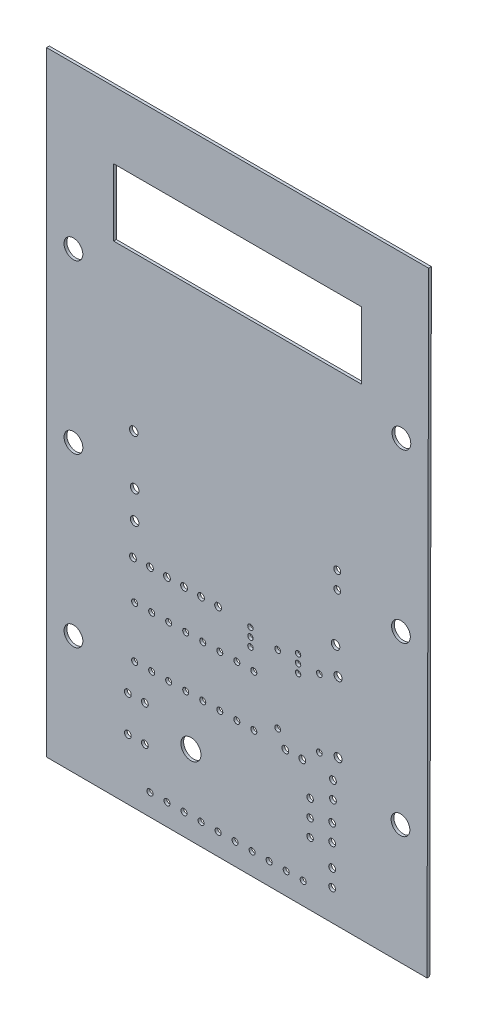
SolidWorks part; units mm, degrees
ref_plane "Front Plane" through (0, 0, 0) normal (0, 0, 1) x (1, 0, 0)
ref_plane "Top Plane" through (0, 0, 0) normal (0, 1, 0) x (1, 0, 0)
ref_plane "Right Plane" through (0, 0, 0) normal (1, 0, 0) x (0, 0, -1)
sketch "Sketch1" plane through (0, 0, 0) normal (0, 0, 1) x (1, 0, 0)
  line L0 (123.1803, 67.5548) -> (123.4282, 159.3916) construction
  line L1 (127.4282, 135.3808) -> (70.4281, 135.3808) construction
  line L2 (74.4281, 159.3813) -> (74.4384, 67.7095) construction
  line L3 (70.4384, 67.7091) -> (127.1803, 67.544)
  line L4 (70.4281, 159.3808) -> (70.4384, 67.7091)
  line L5 (127.1803, 67.544) -> (127.4282, 159.3808)
  line L6 (127.4282, 159.3808) -> (70.4281, 159.3808)
  line L7 (127.4282, 110.3808) -> (70.4281, 110.3808) construction
  line L8 (127.4282, 85.3808) -> (70.4281, 85.3808) construction
  line L9 (117.4309, 149.3808) -> (80.435, 149.3808)
  line L10 (117.4309, 149.3808) -> (117.4309, 139.3808)
  line L11 (117.4309, 139.3808) -> (80.435, 139.3808)
  line L12 (80.435, 149.3808) -> (80.435, 139.3808)
  circle A0 centre (113.792, 110.998) radius 0.508
  circle A1 centre (113.792, 113.538) radius 0.508
  circle A2 centre (113.919, 99.845) radius 0.6
  circle A3 centre (113.538, 103.759) radius 0.635
  circle A4 centre (107.95, 99.822) radius 0.4
  circle A5 centre (111.125, 98.806) radius 0.425
  circle A6 centre (113.919, 89.385) radius 0.6
  circle A7 centre (107.95, 98.552) radius 0.4
  circle A8 centre (111.125, 88.646) radius 0.425
  circle A9 centre (104.902, 98.806) radius 0.425
  circle A10 centre (107.95, 97.282) radius 0.4
  circle A11 centre (100.838, 99.695) radius 0.4
  circle A12 centre (100.838, 98.425) radius 0.4
  circle A13 centre (101.346, 94.234) radius 0.45
  circle A14 centre (104.902, 88.646) radius 0.425
  circle A15 centre (100.838, 97.155) radius 0.4
  circle A16 centre (101.346, 86.614) radius 0.45
  circle A17 centre (113.157, 86.106) radius 0.508
  circle A18 centre (113.157, 83.566) radius 0.508
  circle A19 centre (109.742, 82.0512) radius 0.4826
  circle A20 centre (113.03, 80.518) radius 0.508
  circle A21 centre (113.03, 74.676) radius 0.508
  circle A22 centre (113.03, 72.136) radius 0.508
  circle A23 centre (109.742, 79.5112) radius 0.4826
  circle A24 centre (113.03, 77.978) radius 0.508
  circle A25 centre (108.585, 86.487) radius 0.508
  circle A26 centre (109.742, 76.9712) radius 0.4826
  circle A27 centre (98.806, 86.614) radius 0.45
  circle A28 centre (106.045, 86.487) radius 0.508
  circle A29 centre (106.172, 70.866) radius 0.45
  circle A30 centre (108.712, 70.866) radius 0.45
  circle A31 centre (101.092, 70.866) radius 0.45
  circle A32 centre (103.632, 70.866) radius 0.45
  circle A33 centre (96.266, 94.234) radius 0.45
  circle A34 centre (96.012, 99.949) radius 0.508
  circle A35 centre (93.726, 94.234) radius 0.45
  circle A36 centre (90.932, 99.949) radius 0.508
  circle A37 centre (93.472, 99.949) radius 0.508
  circle A38 centre (98.806, 94.234) radius 0.45
  circle A39 centre (93.726, 86.614) radius 0.45
  circle A40 centre (88.646, 94.234) radius 0.45
  circle A41 centre (91.186, 94.234) radius 0.45
  circle A42 centre (83.566, 104.775) radius 0.635
  circle A43 centre (85.852, 99.949) radius 0.508
  circle A44 centre (83.439, 116.332) radius 0.635
  circle A45 centre (83.566, 108.966) radius 0.635
  circle A46 centre (88.392, 99.949) radius 0.508
  circle A47 centre (86.106, 94.234) radius 0.45
  circle A48 centre (83.312, 99.949) radius 0.508
  circle A49 centre (83.566, 94.234) radius 0.45
  circle A50 centre (91.186, 86.614) radius 0.45
  circle A51 centre (96.266, 86.614) radius 0.45
  circle A52 centre (88.646, 86.614) radius 0.45
  circle A53 centre (91.962, 79.5112) radius 1.5
  circle A54 centre (96.012, 70.866) radius 0.45
  circle A55 centre (98.552, 70.866) radius 0.45
  circle A56 centre (90.932, 70.866) radius 0.45
  circle A57 centre (93.472, 70.866) radius 0.45
  circle A58 centre (86.106, 86.614) radius 0.45
  circle A59 centre (85.09, 82.042) radius 0.508
  circle A60 centre (83.566, 86.614) radius 0.45
  circle A61 centre (82.55, 82.042) radius 0.508
  circle A62 centre (85.852, 70.866) radius 0.45
  circle A63 centre (88.392, 70.866) radius 0.45
  circle A64 centre (82.55, 76.708) radius 0.508
  circle A65 centre (85.09, 76.708) radius 0.508
  circle A66 centre (123.3634, 135.3808) radius 1.4
  circle A67 centre (74.4308, 135.3808) radius 1.4
  circle A68 centre (74.4336, 110.3808) radius 1.4
  circle A69 centre (123.2959, 110.3808) radius 1.4
  circle A70 centre (74.4364, 85.3808) radius 1.4
  circle A71 centre (123.2284, 85.3808) radius 1.4
  dimension "D3" = 2.8
  dimension "D5" = 2.8
  dimension "D1" = 4
  dimension "D4" = 4
  dimension "D2" = 24
  dimension "D6" = 25
  dimension "D7" = 25
extrude "Boss-Extrude1" add sketch "Sketch1" against normal blind 0.4115
